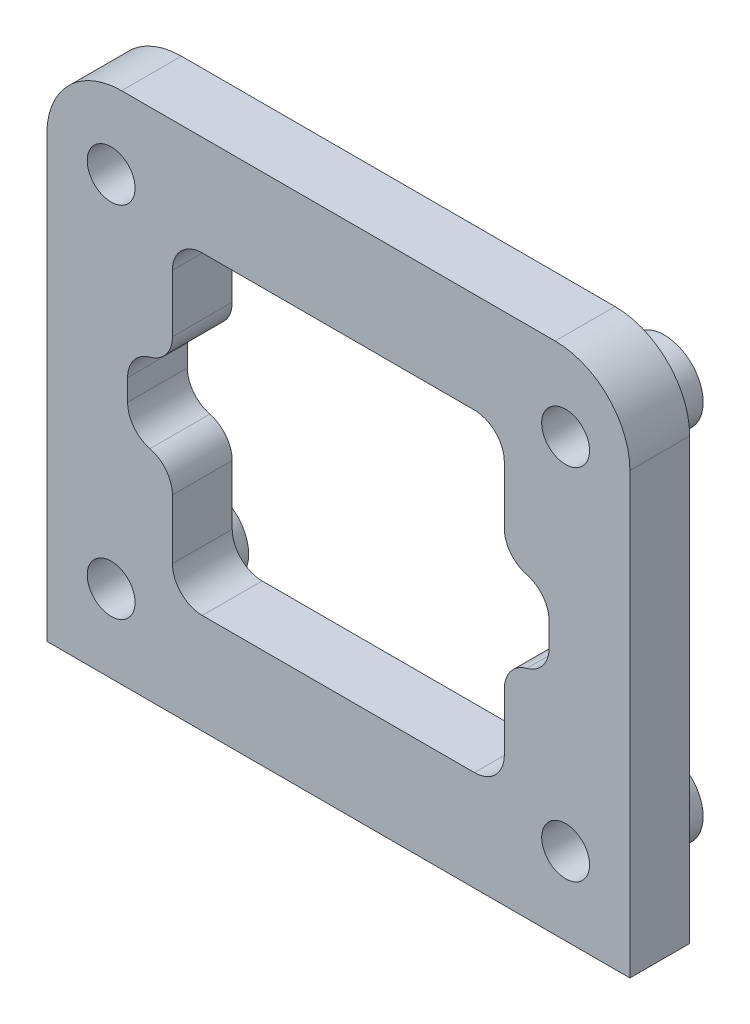
SolidWorks part; units mm, degrees
ref_plane "Front Plane" through (0, 0, 0) normal (0, 0, 1) x (1, 0, 0)
ref_plane "Top Plane" through (0, 0, 0) normal (0, 1, 0) x (1, 0, 0)
ref_plane "Right Plane" through (0, 0, 0) normal (1, 0, 0) x (0, 0, -1)
sketch "Sketch1" plane through (0, 0, 0) normal (0, 0, 1) x (1, 0, 0)
  line L0 (14.3001, 0.1557) -> (11.3001, 0.1557)
  line L2 (19.7001, 14.7057) -> (-19.2999, 14.7057)
  line L3 (19.7001, 14.7057) -> (19.7001, -19.6943)
  line L4 (19.7001, -19.6943) -> (-19.2999, -19.6943)
  line L5 (-10.8999, 8.0057) -> (11.3001, 8.0057)
  line L6 (-13.8999, 0.1557) -> (-13.8999, -5.1443)
  line L7 (-10.8999, -12.9943) -> (11.3001, -12.9943)
  line L8 (-19.2999, 14.7057) -> (-19.2999, -19.6943)
  line L9 (-13.8999, 0.1557) -> (-10.8999, 0.1557)
  line L10 (14.3001, 0.1557) -> (14.3001, -5.1443)
  line L12 (-10.8999, 0.1557) -> (-10.8999, 8.0057)
  line L13 (11.3001, 0.1557) -> (11.3001, 8.0057)
  line L17 (-13.8999, -5.1443) -> (-10.8999, -5.1443)
  line L18 (-10.8999, -12.9943) -> (-10.8999, -5.1443)
  line L21 (14.3001, -5.1443) -> (11.3001, -5.1443)
  line L22 (11.3001, -12.9943) -> (11.3001, -5.1443)
  circle A0 centre (-14.9999, 9.5057) radius 1.6
  circle A1 centre (15.4001, 9.5057) radius 1.6
  circle A2 centre (-14.9999, -14.4943) radius 1.6
  circle A3 centre (15.4001, -14.4943) radius 1.6
  dimension "D9" = 28.2
  dimension "D2" = 30.4
  dimension "D3" = 24
  dimension "D4" = 21
  dimension "D5" = 39
  dimension "D6" = 34.4
  dimension "D7" = 6.7
  dimension "D8" = 6.7
  dimension "D10" = 5.4
  dimension "D11" = 5.4
  dimension "D12" = 22.2
  dimension "D13" = 3
  dimension "D14" = 7.85
  dimension "D15" = 3
  dimension "D16" = 7.85
  dimension "D17" = 4.3
  dimension "D18" = 5.2
  dimension "D19" = 5.2
  dimension "D20" = 4.3
extrude "Boss-Extrude5" add sketch "Sketch1" along normal blind 4
fillet "Fillet1" radius 5 2 edges at (-19.2999, 14.7057, 2) (19.7001, 14.7057, 2)
sketch "Sketch4" plane through (0, 0, 0) normal (0, 0, 1) x (1, 0, 0)
  circle A0 centre (15.4001, 9.5057) radius 1.6
  circle A1 centre (15.4001, 9.5057) radius 2.6
  circle A2 centre (-14.9999, 9.5057) radius 1.6
  circle A3 centre (-14.9999, 9.5057) radius 2.6
  circle A4 centre (15.4001, -14.4943) radius 1.6
  circle A5 centre (15.4001, -14.4943) radius 2.6
  circle A6 centre (-14.9999, -14.4943) radius 1.6
  circle A7 centre (-14.9999, -14.4943) radius 2.6
extrude "Boss-Extrude6" add sketch "Sketch4" against normal blind 2.6
fillet "Fillet4" radius 2 1 edges at (-10.8999, 8.0057, 2)
fillet "Fillet5" radius 2 1 edges at (-10.8999, 0.1557, 2)
fillet "Fillet6" radius 2 1 edges at (-13.8999, 0.1557, 2)
fillet "Fillet8" radius 2 1 edges at (-13.8999, -5.1443, 2)
fillet "Fillet9" radius 2 1 edges at (-10.8999, -5.1443, 2)
fillet "Fillet10" radius 2 1 edges at (-10.8999, -12.9943, 2)
fillet "Fillet11" radius 2 1 edges at (11.3001, -5.1443, 2)
fillet "Fillet12" radius 2 1 edges at (11.3001, 0.1557, 2)
fillet "Fillet13" radius 2 1 edges at (11.3001, -12.9943, 2)
fillet "Fillet14" radius 2 1 edges at (14.3001, 0.1557, 2)
fillet "Fillet15" radius 2 1 edges at (11.3001, 8.0057, 2)
fillet "Fillet16" radius 2 1 edges at (14.3001, -5.1443, 2)
